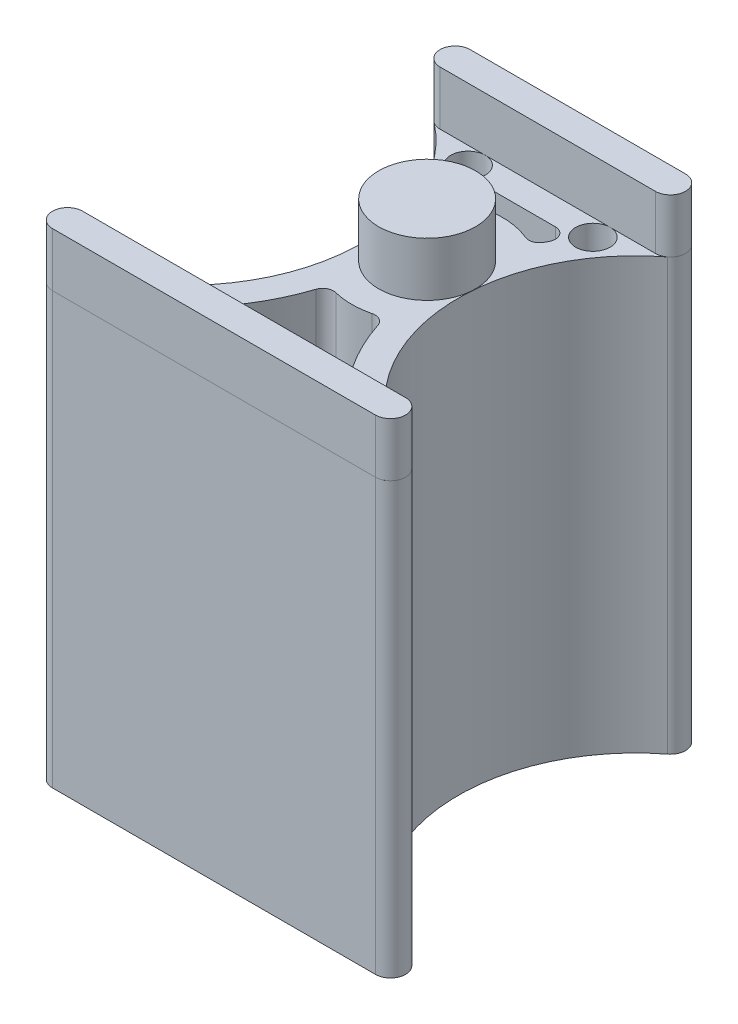
SolidWorks part; units mm, degrees
ref_plane "Front Plane" through (0, 0, 0) normal (0, 0, 1) x (1, 0, 0)
ref_plane "Top Plane" through (0, 0, 0) normal (0, 1, 0) x (1, 0, 0)
ref_plane "Right Plane" through (0, 0, 0) normal (1, 0, 0) x (0, 0, -1)
sketch "Sketch1" plane through (0, 0, 0) normal (0, 1, 0) x (1, 0, 0)
  line L0 (-10, 12.6) -> (10, 12.6) construction
  line L1 (-10, 14) -> (10, 14)
  line L2 (-10, 11.2) -> (10, 11.2)
  line L3 (-15, -18.4) -> (15, -18.4) construction
  line L4 (-15, -17) -> (15, -17)
  line L5 (-15, -19.8) -> (15, -19.8)
  circle A0 centre (0, 0) radius 4.5
  arc A1 (-10, 14) -> (-10, 11.2) centre (-10, 12.6) ccw
  arc A2 (10, 11.2) -> (10, 14) centre (10, 12.6) ccw
  arc A3 (-15, -17) -> (-15, -19.8) centre (-15, -18.4) ccw
  arc A4 (15, -19.8) -> (15, -17) centre (15, -18.4) ccw
  point P5 (0, 12.6)
  point P10 (0, -18.4)
  point P17 (0, 0)
  dimension "D1" = 9
  dimension "D6" = 30
  dimension "D2" = 12.6
  dimension "D3" = 2.8
  dimension "D4" = 20
  dimension "D5" = 2.8
  dimension "D7" = 18.4
extrude "Boss-Extrude1" add sketch "Sketch1" along normal blind 5
sketch "Sketch2" plane through (0, 0, 0) normal (0, -1, 0) x (1, 0, 0)
  line L0 (-15, 19.8) -> (15, 19.8)
  line L2 (-10, -14) -> (10, -14)
  line L4 (-15, 17) -> (15, 17)
  line L5 (15, 19.8) -> (-15, 19.8)
  line L7 (15, 19.8) -> (-15, 19.8)
  line L10 (-10, -14) -> (10, -14)
  line L11 (10, -11.2) -> (-10, -11.2)
  line L12 (-10, -14) -> (10, -14)
  arc A0 (-10.8403, -11.4802) -> (-15.4626, 17.0786) centre (-20.9014, 1.5449) ccw
  circle A1 centre (0, 0) radius 4.5 construction
  arc A2 (15.4626, 17.0786) -> (10.8403, -11.4802) centre (20.9014, 1.5449) ccw
  arc A4 (-15, 19.8) -> (-15, 17) centre (-15, 18.4) ccw
  arc A5 (15, 17) -> (15, 19.8) centre (15, 18.4) ccw
  arc A6 (-15, 19.8) -> (-15.4626, 17.0786) centre (-15, 18.4) ccw
  arc A7 (15.4626, 17.0786) -> (15, 19.8) centre (15, 18.4) ccw
  arc A9 (-10, -11.2) -> (-10, -14) centre (-10, -12.6) ccw
  arc A10 (-10, -11.2) -> (-10, -14) centre (-10, -12.6) ccw
  arc A11 (10, -14) -> (10, -11.2) centre (10, -12.6) ccw
  arc A14 (-10.8403, -11.4802) -> (-10, -14) centre (-10, -12.6) ccw
  arc A16 (10, -14) -> (10, -11.2) centre (10, -12.6) ccw
  arc A17 (10, -14) -> (10.8403, -11.4802) centre (10, -12.6) ccw
  arc M11 (-15, 19.8) -> (-15, 17) centre (-15, 18.4) ccw
  line M12 (-15, 17) -> (15, 17)
  arc M13 (15, 17) -> (15, 19.8) centre (15, 18.4) ccw
  line M14 (15, 19.8) -> (-15, 19.8)
  dimension "D1" = 0
  dimension "D2" = 0
  dimension "D3" = 0
  dimension "D4" = 0
extrude "Boss-Extrude2" add sketch "Sketch2" along normal blind 40 separate body contours M14 M11 M12 M13 | L2 A17 A2 A0 A14 M13 M12 M11
sketch "Sketch3" plane through (0, 0, 0) normal (0, 1, 0) x (1, 0, 0)
  line L2 (15, -14.5) -> (-15, -14.5)
  line L3 (15, -14.5) -> (-15, -14.5)
  arc A11 (-14.6365, -19.4382) -> (-9.312, 13.4587) centre (-20.9014, -1.5449) ccw
  arc A12 (-14.6365, -19.4382) -> (-9.312, 13.4587) centre (-20.9014, -1.5449) ccw
  arc A14 (9.312, 13.4587) -> (14.6365, -19.4382) centre (20.9014, -1.5449) ccw
  arc A15 (9.312, 13.4587) -> (14.6365, -19.4382) centre (20.9014, -1.5449) ccw
  circle A17 centre (0, 0) radius 7
  circle A18 centre (0, 0) radius 7
  dimension "D1" = 2.5
  dimension "D2" = 2.5
  dimension "D3" = 2.5
  dimension "D4" = 2.5
extrude "Cut-Extrude1" cut sketch "Sketch3" against normal through all contours A18 A12 L3 A15
fillet "Fillet1" radius 1 4 edges at (2.6016, -20, 6.4986) (-2.6016, -20, 6.4986) (7.06, -20, 14.5) (-7.06, -20, 14.5)
sketch "Sketch4" plane through (0, 0, 0) normal (0, 1, 0) x (1, 0, 0)
  line L10 (-10, 8.7) -> (10, 8.7)
  line L11 (-10, 8.7) -> (10, 8.7)
  arc A2 (-14.6365, -19.4382) -> (-9.312, 13.4587) centre (-20.9014, -1.5449) ccw
  arc A3 (-14.6365, -19.4382) -> (-9.312, 13.4587) centre (-20.9014, -1.5449) ccw
  arc A5 (9.312, 13.4587) -> (14.6365, -19.4382) centre (20.9014, -1.5449) ccw
  arc A6 (9.312, 13.4587) -> (14.6365, -19.4382) centre (20.9014, -1.5449) ccw
  circle A14 centre (0, 0) radius 7
  circle A15 centre (0, 0) radius 7
  dimension "D1" = 2.5
  dimension "D2" = 2.5
  dimension "D3" = 2.5
  dimension "D4" = 2.5
extrude "Cut-Extrude2" cut sketch "Sketch4" against normal through all contours A15 A6 L11 A3
fillet "Fillet2" radius 1 4 edges at (3.5288, -20, -6.0455) (-3.5288, -20, -6.0455) (4.9495, -20, -8.7) (-4.9495, -20, -8.7)
sketch "Sketch5" plane through (0, 0, 0) normal (0, 1, 0) x (1, 0, 0)
  line L0 (-10, 11.2) -> (10, 11.2) construction
  line L1 (15, -17) -> (-15, -17) construction
  circle A0 centre (-7.7, -15.4) radius 1.6
  circle A1 centre (7.7, -15.4) radius 1.6
  circle A2 centre (-5.8, 9.6) radius 1.6
  circle A3 centre (5.8, 9.6) radius 1.6
  point P8 (-5.8632, 9.1421)
  point P9 (0, 0)
  point P10 (-7.8476, -14.8519)
  point P11 (7.6672, -14.8519)
  point P13 (0, 0)
  dimension "D1" = 3.2
  dimension "D2" = 7.7
  dimension "D3" = 7.7
  dimension "D4" = 5.8
  dimension "D5" = 5.8
extrude "Cut-Extrude3" cut sketch "Sketch5" against normal through all
